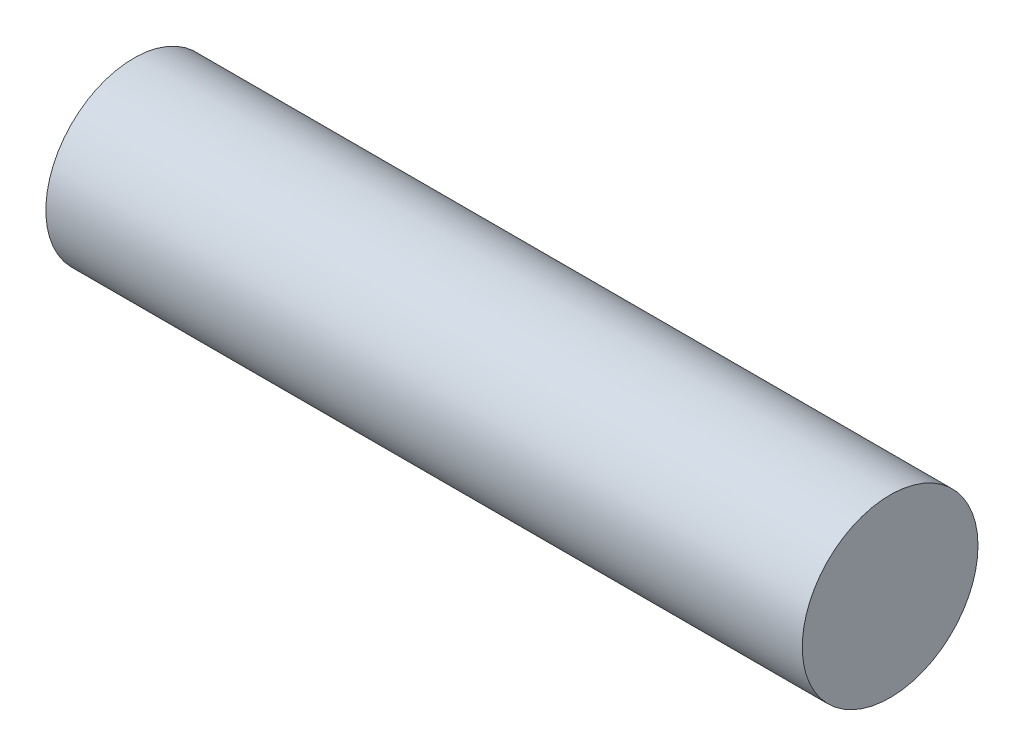
SolidWorks part; units mm, degrees
ref_plane "Front Plane" through (0, 0, 0) normal (0, 0, 1) x (1, 0, 0)
ref_plane "Top Plane" through (0, 0, 0) normal (0, 1, 0) x (1, 0, 0)
ref_plane "Right Plane" through (0, 0, 0) normal (1, 0, 0) x (0, 0, -1)
sketch "Sketch1" plane through (0, 0, 0) normal (1, 0, 0) x (0, 0, -1)
  circle A0 centre (0, 0) radius 4.7625
extrude "Boss-Extrude1" add sketch "Sketch1" along normal blind 41
